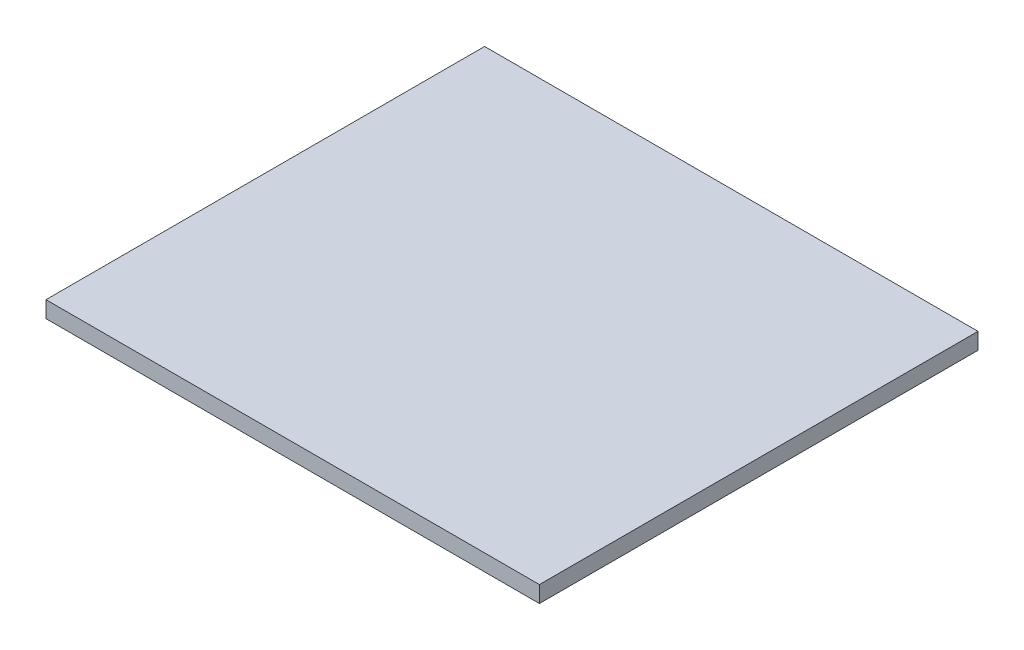
SolidWorks part; units mm, degrees
ref_plane "前视基准面" through (0, 0, 0) normal (0, 0, 1) x (1, 0, 0)
ref_plane "上视基准面" through (0, 0, 0) normal (0, 1, 0) x (1, 0, 0)
ref_plane "右视基准面" through (0, 0, 0) normal (1, 0, 0) x (0, 0, -1)
other "Configuration Table"
sketch "草图1" plane through (0, 0, 0) normal (0, 1, 0) x (1, 0, 0)
  line L1 (-45, -40) -> (45, -40)
  line L2 (-45, -40) -> (-45, 40)
  line L3 (-45, 40) -> (45, 40)
  line L4 (45, -40) -> (45, 40)
  line L5 (-45, -40) -> (45, 40) construction
  line L6 (-45, 40) -> (45, -40) construction
  point P0 (0, 0)
  dimension "D1" = 90
  dimension "D2" = 80
extrude "凸台-拉伸1" add sketch "草图1" along normal blind 3
